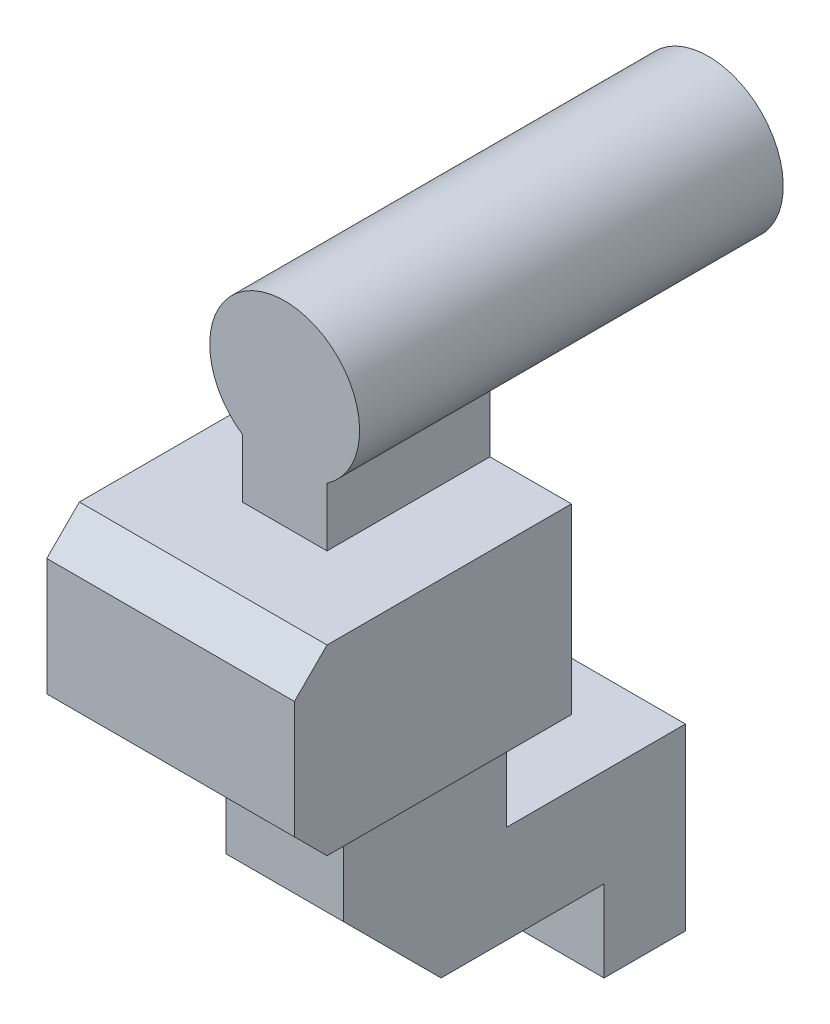
SolidWorks part; units mm, degrees
ref_plane "Płaszczyzna przednia" through (0, 0, 0) normal (0, 0, 1) x (1, 0, 0)
ref_plane "Płaszczyzna górna" through (0, 0, 0) normal (0, 1, 0) x (1, 0, 0)
ref_plane "Płaszczyzna prawa" through (0, 0, 0) normal (1, 0, 0) x (0, 0, -1)
sketch "Szkic1" plane through (0, 0, 0) normal (0, 0, 1) x (1, 0, 0)
  line L1 (-3.8, 2.8) -> (3.8, 2.8)
  line L2 (-3.8, 2.8) -> (-3.8, -2.8)
  line L3 (-3.8, -2.8) -> (3.8, -2.8)
  line L4 (3.8, 2.8) -> (3.8, -2.8)
  line L5 (-3.8, 2.8) -> (3.8, -2.8) construction
  line L6 (-3.8, -2.8) -> (3.8, 2.8) construction
  point P0 (0, 0)
  dimension "D1" = 7.6
  dimension "D2" = 5.6
extrude "Dodanie-wyciągnięcie1" add sketch "Szkic1" along normal blind 5
sketch "Szkic2" plane through (0, 0, 5) normal (0, 0, 1) x (1, 0, 0)
  line L1 (0, 0) -> (0, 10.8725) construction
  line L8 (3.8, 2.8) -> (-3.8, 2.8) construction
  line L9 (1.3, 2.8) -> (-1.3, 2.8)
  line L10 (1.3, 2.8) -> (1.3, 4.6)
  line L11 (1.3, 4.6) -> (-1.3, 4.6)
  line L12 (-1.3, 2.8) -> (-1.3, 4.6)
  line L13 (1.3, 2.8) -> (-1.3, 4.6) construction
  line L14 (1.3, 4.6) -> (-1.3, 2.8) construction
  circle A1 centre (0, 6.4974) radius 2.3
  point P12 (0, 3.7)
  dimension "D4" = 4.6
  dimension "D5" = 2.6
  dimension "D6" = 1.8
extrude "Dodanie-wyciągnięcie2" add sketch "Szkic2" against normal up to vertex (5 mm away)
sketch "Szkic3" plane through (0, 0, 5) normal (0, 0, 1) x (1, 0, 0)
  line L0 (-1.8, -2.8) -> (-1.8, -9.8)
  line L2 (-1.8, -9.8) -> (1.8, -9.8)
  line L3 (1.8, -9.8) -> (1.8, -2.8)
  line L4 (-3.8, -2.8) -> (3.8, -2.8) construction
  line L5 (-1.8, -2.8) -> (1.8, -2.8)
  line L6 (0, 0) -> (0, -2.8) construction
  dimension "D1" = 3.6
  dimension "D2" = 7
extrude "Dodanie-wyciągnięcie3" add sketch "Szkic3" against normal up to vertex (5 mm away)
sketch "Szkic4" plane through (0, 0, 0) normal (0, 0, -1) x (-1, 0, 0)
  circle A1 centre (0, 6.4974) radius 2.3
extrude "Dodanie-wyciągnięcie4" add sketch "Szkic4" along normal blind 8
chamfer "Sfazowanie1" distance 3 angle 45 1 edges at (0, -9.8, 5)
sketch "Szkic5" plane through (3.8, 0, 0) normal (1, 0, 0) x (0, 0, -1)
  line L0 (-5, 2.8) -> (-8.5, 2.8)
  line L1 (-5, 2.8) -> (0, 2.8) construction
  line L2 (-8.5, 2.8) -> (-8.5, -2.8)
  line L3 (-8.5, -2.8) -> (-5, -2.8)
  line L4 (-5, -2.8) -> (-5, 2.8) construction
  line L5 (-5, -2.8) -> (-5, 2.8)
  line L6 (-5, -2.8) -> (0, -2.8) construction
  dimension "D1" = 3.5
extrude "Dodanie-wyciągnięcie5" add sketch "Szkic5" against normal up to vertex (7.6 mm away)
sketch "Szkic6" plane through (-1.8, 0, 0) normal (-1, 0, 0) x (0, 0, 1)
  line L0 (0, -9.8) -> (-3, -9.8)
  line L1 (0, 2.8) -> (0, -2.8) construction
  line L2 (-3, -9.8) -> (-3, -12.3)
  line L3 (-3, -12.3) -> (-5.5, -12.3)
  line L4 (-5.5, -12.3) -> (-5.5, -6.8)
  line L5 (-5.5, -6.8) -> (0, -6.8)
  line L6 (0, -9.8) -> (0, -6.8)
  dimension "D1" = 3
  dimension "D2" = 3
  dimension "D3" = 2.5
  dimension "D4" = 2.5
extrude "Dodanie-wyciągnięcie6" add sketch "Szkic6" against normal up to vertex (3.6 mm away) up to point (1.8, -9.8, 0)
chamfer "Sfazowanie3" distance 1 angle 45 2 edges at (0, -2.8, 8.5) (0, 2.8, 8.5)
